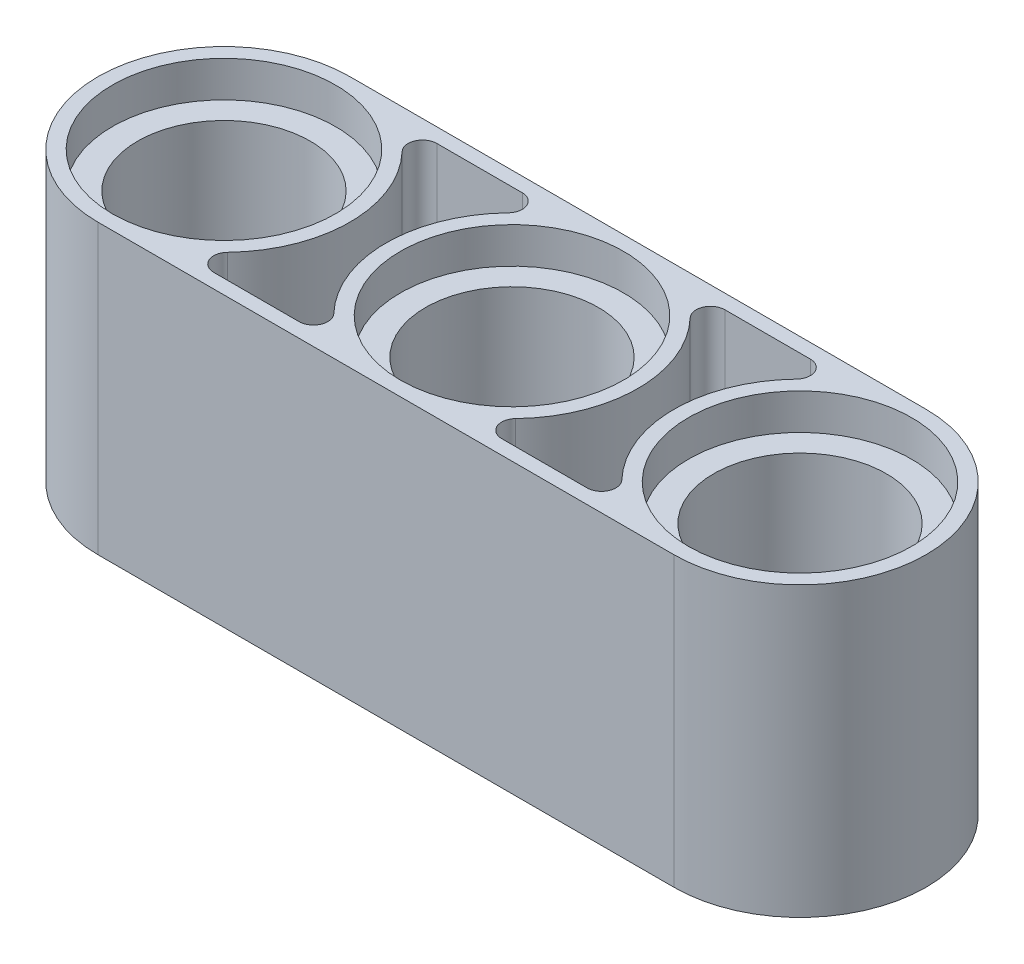
SolidWorks part; units mm, degrees
ref_plane "Front Plane" through (0, 0, 0) normal (0, 0, 1) x (1, 0, 0)
ref_plane "Top Plane" through (0, 0, 0) normal (0, 1, 0) x (1, 0, 0)
ref_plane "Right Plane" through (0, 0, 0) normal (1, 0, 0) x (0, 0, -1)
sketch "Sketch2" plane through (0, 0, 0) normal (0, 1, 0) x (1, 0, 0)
  line L0 (0, 0) -> (16, 0) construction
  line L1 (0, 3.5) -> (16, 3.5)
  line L2 (0, -3.5) -> (16, -3.5)
  arc A0 (0, 3.5) -> (0, -3.5) centre (0, 0) ccw
  arc A1 (16, -3.5) -> (16, 3.5) centre (16, 0) ccw
  point P3 (8, 0)
  point P8 (-3.5, 0)
  point P9 (19.5, 0)
  dimension "D1" = 23
  dimension "D2" = 7
extrude "Boss-Extrude1" add sketch "Sketch2" along normal mid plane 8
sketch "Sketch3" plane through (0, 4, 0) normal (0, 1, 0) x (1, 0, 0)
  circle A0 centre (0, 0) radius 3.1
  dimension "D1" = 6.2
extrude "Cut-Extrude1" cut sketch "Sketch3" against normal blind 1
sketch "Sketch4" plane through (0, 4, 0) normal (0, 1, 0) x (1, 0, 0)
  circle A0 centre (0, 0) radius 2.4
  dimension "D1" = 4.8
extrude "Cut-Extrude2" cut sketch "Sketch4" against normal through all
sketch "Sketch7" plane through (0, -4, 0) normal (0, -1, 0) x (-1, 0, 0)
  circle A0 centre (0, 0) radius 3.1
  dimension "D1" = 6.2
extrude "Cut-Extrude4" cut sketch "Sketch7" against normal blind 1
pattern_linear "LPattern3" count 3 spacing 8 along (1, 0, 0) of "Cut-Extrude4", "Cut-Extrude2", "Cut-Extrude1"
sketch "Sketch8" plane through (0, 4, 0) normal (0, 1, 0) x (1, 0, 0)
  line L0 (2.8142, 3.1) -> (5.1858, 3.1)
  line L1 (2.8142, -3.1) -> (5.1858, -3.1)
  arc A0 (2.5256, -2.4231) -> (2.5256, 2.4231) centre (0, 0) ccw
  arc A1 (5.4744, 2.4231) -> (5.4744, -2.4231) centre (8, 0) ccw
  arc A6 (2.5256, -2.4231) -> (2.8142, -3.1) centre (2.8142, -2.7) ccw
  arc A7 (5.1858, -3.1) -> (5.4744, -2.4231) centre (5.1858, -2.7) ccw
  arc A8 (5.1858, 3.1) -> (5.4744, 2.4231) centre (5.1858, 2.7) cw
  arc A9 (2.5256, 2.4231) -> (2.8142, 3.1) centre (2.8142, 2.7) cw
  dimension "D1" = 7
  dimension "D2" = 7
  dimension "D3" = 0.4
extrude "Cut-Extrude5" cut sketch "Sketch8" against normal through all
pattern_linear "LPattern4" count 2 spacing 8 along (1, 0, 0) of "Cut-Extrude5"
